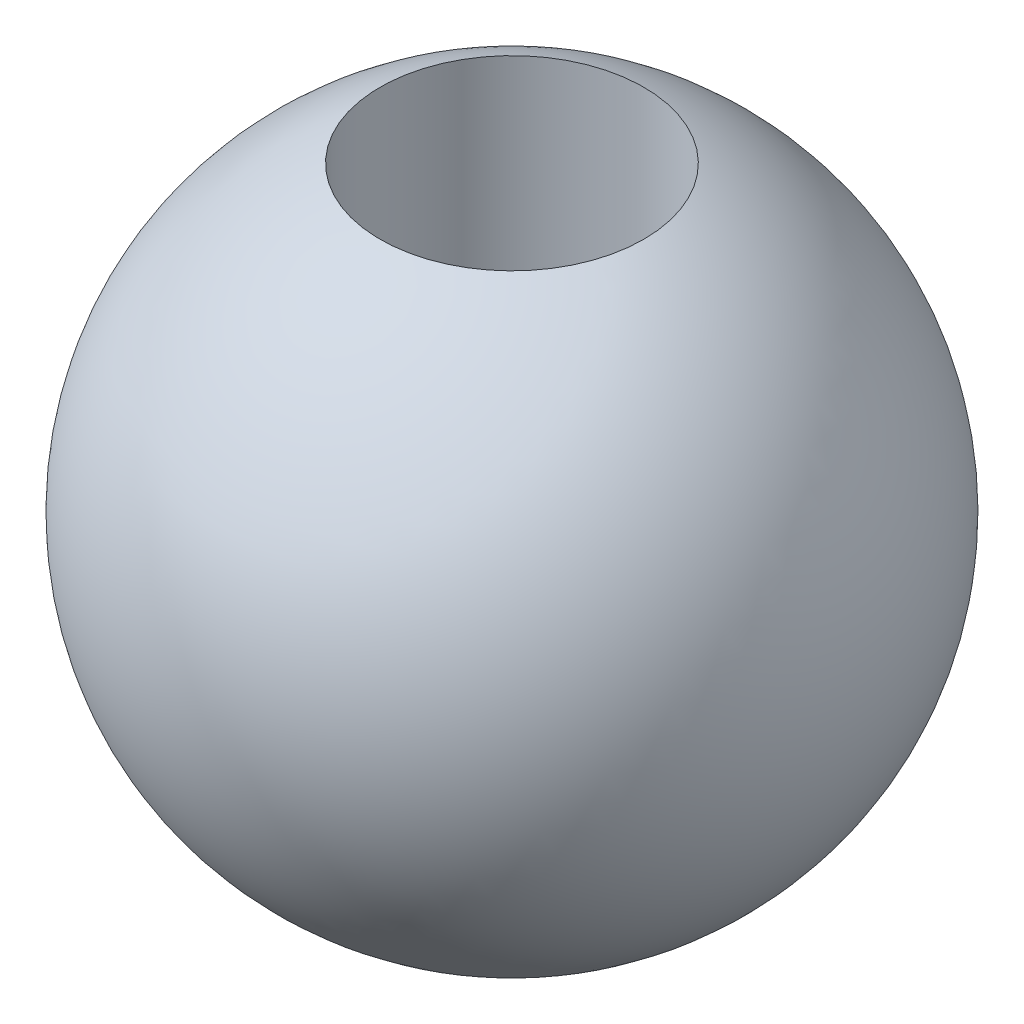
SolidWorks part; units mm, degrees
ref_plane "Plan de face" through (0, 0, 0) normal (0, 0, 1) x (1, 0, 0)
ref_plane "Plan de dessus" through (0, 0, 0) normal (0, 1, 0) x (1, 0, 0)
ref_plane "Plan de droite" through (0, 0, 0) normal (1, 0, 0) x (0, 0, -1)
sketch "Esquisse1" plane through (0, 0, 0) normal (0, 0, 1) x (1, 0, 0)
  line L3 (0, -2.5) -> (0, 2.5)
  arc A0 (0, 2.5) -> (0, -2.5) centre (0, 0) ccw
  dimension "D1" = 5
revolve "Révolution1" add sketch "Esquisse1" angle 360 about L3
sketch "Esquisse2" plane through (0, 0, 0) normal (0, 1, 0) x (1, 0, 0)
  circle A0 centre (0, 0) radius 1
  dimension "D1" = 2
extrude "Enlèv. mat.-Extru.1" cut sketch "Esquisse2" against normal mid plane 10
